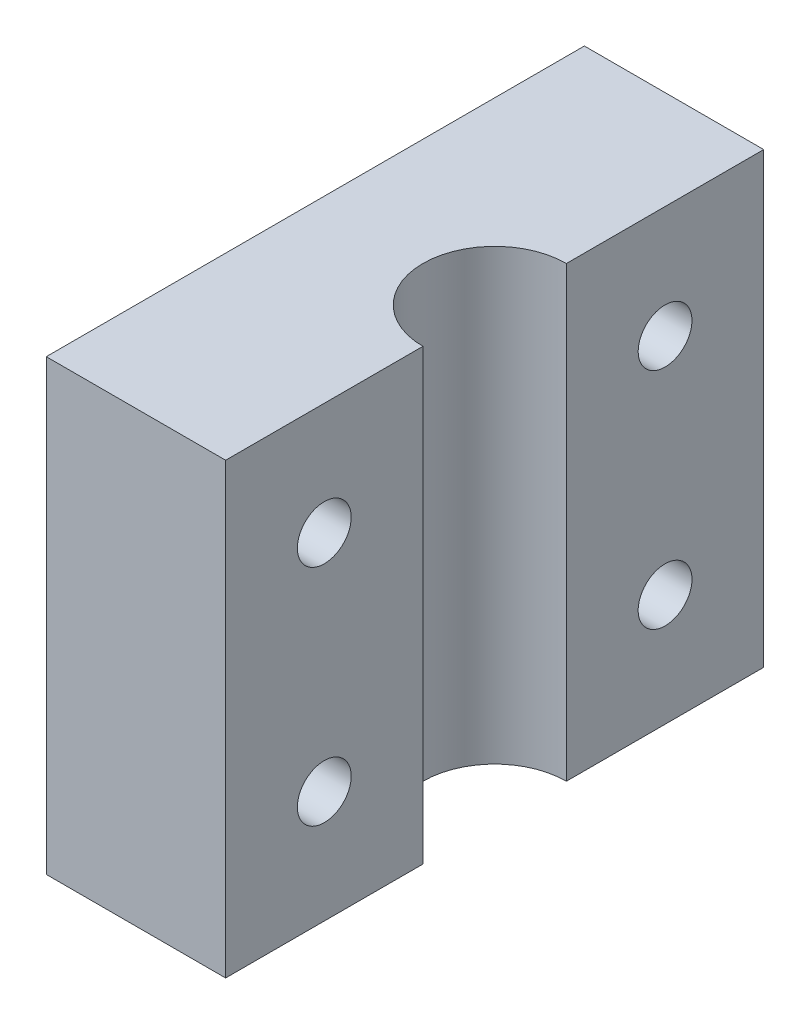
SolidWorks part; units mm, degrees
ref_plane "정면" through (0, 0, 0) normal (0, 0, 1) x (1, 0, 0)
ref_plane "윗면" through (0, 0, 0) normal (0, 1, 0) x (1, 0, 0)
ref_plane "우측면" through (0, 0, 0) normal (1, 0, 0) x (0, 0, -1)
sketch "스케치1" plane through (0, 0, 0) normal (1, 0, 0) x (0, 0, -1)
  line L1 (0, 0) -> (30, 0)
  line L2 (0, 0) -> (0, 25)
  line L3 (0, 25) -> (30, 25)
  line L4 (30, 0) -> (30, 25)
  dimension "D1" = 30
  dimension "D2" = 25
extrude "보스-돌출1" add sketch "스케치1" along normal blind 10
sketch "스케치2" plane through (0, 25, 0) normal (0, 1, 0) x (1, 0, 0)
  line L0 (10, 30) -> (10, 0) construction
  circle A0 centre (10, 15) radius 4
  dimension "D1" = 8
extrude "컷-돌출1" cut sketch "스케치2" against normal through all
sketch "스케치3" plane through (10, 0, 0) normal (1, 0, 0) x (0, 0, -1)
  line L0 (15, 25) -> (15, 0) construction
  line L1 (19, 25) -> (11, 25) construction
  line L2 (11, 0) -> (19, 0) construction
  line L3 (0, 12.5) -> (30, 12.5) construction
  line L4 (0, 25) -> (0, 0) construction
  line L5 (30, 0) -> (30, 25) construction
  line L6 (0, 0) -> (11, 0) construction
  line L7 (11, 0) -> (11, 25) construction
  line L8 (11, 25) -> (0, 25) construction
  line L9 (30, 25) -> (19, 25) construction
  line L10 (19, 25) -> (19, 0) construction
  line L11 (19, 0) -> (30, 0) construction
  line L12 (0, 0) -> (11, 0)
  line L13 (11, 0) -> (11, 25)
  line L14 (11, 25) -> (0, 25)
  line L15 (0, 12.5) -> (0, 25)
  line L16 (30, 25) -> (19, 25)
  line L17 (19, 25) -> (19, 0)
  line L18 (19, 0) -> (30, 0)
  line L19 (30, 0) -> (30, 25)
  line L21 (0, 18.75) -> (5.5, 18.75) construction
  circle A0 centre (5.5, 18.75) radius 1.5
  circle A1 centre (24.5, 18.75) radius 1.5
  circle A2 centre (5.5, 6.25) radius 1.5
  circle A3 centre (24.5, 6.25) radius 1.5
  dimension "D2" = 3
  dimension "D1" = 19
extrude "컷-돌출2" cut sketch "스케치3" against normal through all contours A0 | A2 | A3 | A1
